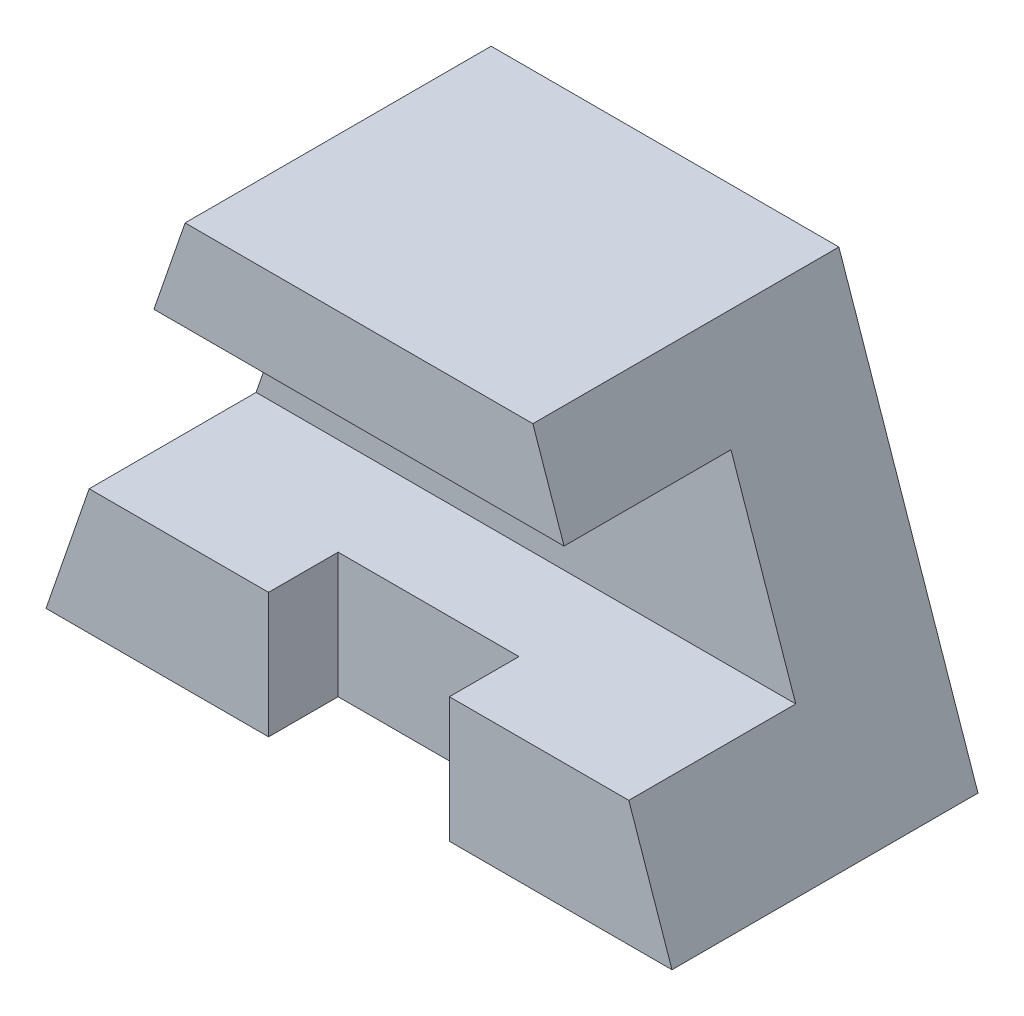
SolidWorks part; units mm, degrees
ref_plane "Front Plane" through (0, 0, 0) normal (0, 0, 1) x (1, 0, 0)
ref_plane "Top Plane" through (0, 0, 0) normal (0, 1, 0) x (1, 0, 0)
ref_plane "Right Plane" through (0, 0, 0) normal (1, 0, 0) x (0, 0, -1)
sketch "Sketch1" plane through (0, 0, 0) normal (0, 0, 1) x (1, 0, 0)
  line L0 (-45, 0) -> (45, 0)
  line L1 (45, 0) -> (25, 58)
  line L2 (25, 58) -> (-25, 58)
  line L3 (-25, 58) -> (-45, 0)
  point P3 (0, 0)
  point P6 (0, 58)
  dimension "D1" = 90
  dimension "D2" = 50
  dimension "D3" = 58
extrude "Boss-Extrude1" add sketch "Sketch1" along normal blind 44
sketch "Sketch2" plane through (0, 0, 0) normal (1, 0, 0) x (0, 0, -1)
  line L0 (-44, 18) -> (-20, 18)
  line L1 (-44, 58) -> (-44, 0) construction
  line L2 (-20, 18) -> (-20, 45)
  line L3 (-20, 45) -> (-44, 45)
  line L4 (-44, 45) -> (-44, 18)
  line L5 (-44, 0) -> (0, 0) construction
  dimension "D1" = 18
  dimension "D2" = 24
  dimension "D3" = 27
extrude "Cut-Extrude1" cut sketch "Sketch2" against normal through all both and the other way through all
sketch "Sketch3" plane through (0, 0, 44) normal (0, 0, 1) x (1, 0, 0)
  line L0 (-13, 18) -> (-13, 0)
  line L1 (-38.7931, 18) -> (38.7931, 18) construction
  line L2 (-45, 0) -> (45, 0) construction
  line L3 (-13, 0) -> (13, 0)
  line L4 (13, 0) -> (13, 18)
  line L5 (-38.7931, 18) -> (38.7931, 18) construction
  line L6 (13, 18) -> (-13, 18)
  dimension "D1" = 32
  dimension "D2" = 26
extrude "Cut-Extrude2" cut sketch "Sketch3" against normal blind 10
